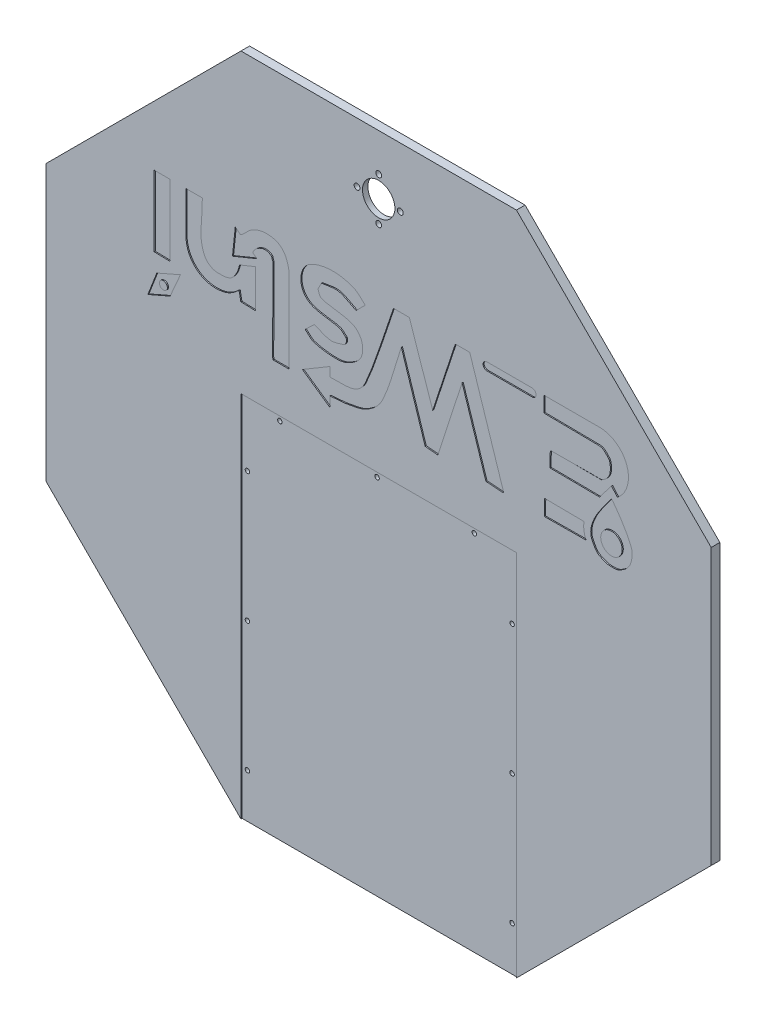
SolidWorks part; units mm, degrees
ref_plane "Front Plane" through (0, 0, 0) normal (0, 0, 1) x (1, 0, 0)
ref_plane "Top Plane" through (0, 0, 0) normal (0, 1, 0) x (1, 0, 0)
ref_plane "Right Plane" through (0, 0, 0) normal (1, 0, 0) x (0, 0, -1)
sketch "Sketch1" plane through (0, 0, 0) normal (0, 0, 1) x (1, 0, 0)
  line L1 (307.8122, -127.5) -> (307.8122, 127.5)
  line L2 (307.8122, 127.5) -> (127.5, 307.8122)
  line L3 (127.5, 307.8122) -> (-127.5, 307.8122)
  line L4 (-127.5, 307.8122) -> (-307.8122, 127.5)
  line L5 (-307.8122, 127.5) -> (-307.8122, -127.5)
  line L6 (-307.8122, -127.5) -> (-127.5, -307.8122)
  line L7 (-127.5, -307.8122) -> (127.5, -307.8122)
  line L8 (127.5, -307.8122) -> (307.8122, -127.5)
  circle A1 centre (0, 0) radius 333.1736 construction
  dimension "D1" = 255
extrude "Boss-Extrude1" add sketch "Sketch1" along normal blind 8
sketch "Sketch2" plane through (0, 0, 0) normal (0, 0, -1) x (-1, 0, 0)
  line L0 (-247.7082, 159.3198) -> (-261.8503, 173.4619)
  line L1 (-247.7082, 159.3198) -> (-159.3198, 247.7082)
  line L2 (-261.8503, 173.4619) -> (-173.4619, 261.8503)
  line L3 (-159.3198, 247.7082) -> (-173.4619, 261.8503)
  line L4 (-307.8122, 127.5) -> (-127.5, 307.8122) construction
  line L6 (-217.6561, 217.6561) -> (-147.1936, 147.1936) construction
  dimension "D1" = 20
  dimension "D2" = 125
  dimension "D3" = 62.5
sketch "Sketch3" plane through (0, 0, 0) normal (0, 0, -1) x (-1, 0, 0)
  line L2 (-127.5, 307.8122) -> (127.5, 307.8122) construction
  circle A0 centre (0.0005, 252.8122) radius 25
  dimension "D1" = 55
extrude "Cut-Extrude1" cut sketch "Sketch3" against normal blind 3
sketch "Sketch4" plane through (0, 0, 3) normal (0, 0, -1) x (-1, 0, 0)
  line L0 (0.0005, 252.8122) -> (0.0005, 272.8122)
  circle A0 centre (0.0005, 252.8122) radius 15
  circle A1 centre (297.8122, -0.0005) radius 2.7032
  circle A2 centre (0.0005, 272.8122) radius 2.7032
  circle A3 centre (-0.0005, -297.8122) radius 2.7032
  circle A4 centre (-297.8122, 0.0005) radius 2.7032
  circle A5 centre (20.0005, 252.8122) radius 2.7032
  circle A6 centre (0.0005, 232.8122) radius 2.7032
  circle A7 centre (-19.9995, 252.8122) radius 2.7032
  point P14 (0, 0)
  point P21 (0.0005, 252.8122)
  dimension "D1" = 30
  dimension "D2" = 20
  dimension "D3" = 5.4065
  dimension "D4" = 4
extrude "Cut-Extrude2" cut sketch "Sketch4" against normal blind 192
sketch "Sketch5" plane through (0, 0, 3) normal (0, 0, -1) x (-1, 0, 0)
  circle A0 centre (0.0005, 252.8122) radius 15
  dimension "D1" = 30
extrude "Cut-Extrude3" cut sketch "Sketch5" against normal blind 192
sketch "Esquisse2" plane through (0, 0, 8) normal (0, 0, 1) x (1, 0, 0)
  line L5 (-127.5, -307.8122) -> (127.5, -307.8122)
  line L6 (127.5, -307.8122) -> (127.5, 33.1878)
  line L7 (127.5, 33.1878) -> (-127.5, 33.1878)
  line L8 (-127.5, 33.1878) -> (-127.5, -307.8122)
  dimension "D1" = 341
extrude "Enlèv. mat.-Extru.2" cut sketch "Esquisse2" against normal blind 1
sketch "Esquisse5" plane through (0, 0, 8) normal (0, 0, 1) x (1, 0, 0)
  line L0 (-908.6273, -471.0171) -> (71.3727, -471.0171) construction
  line L1 (-83.5198, -66.191) -> (-1046.1864, -66.191) construction
  line L2 (-45.2302, 63.2955) -> (-70.6032, 80.9463)
  line L3 (-70.6032, 80.9463) -> (-45.2302, 96.023)
  line L4 (-45.2302, 96.023) -> (-45.2302, 87.6397)
  line L5 (13.7126, 172.142) -> (28.3699, 172.142)
  line L6 (28.3699, 172.142) -> (50.0106, 108.5256)
  line L7 (50.0106, 108.5256) -> (70.9709, 172.142)
  line L8 (70.9709, 172.142) -> (84.2845, 172.142)
  line L9 (84.2845, 172.142) -> (115.8333, 75.0627)
  line L10 (115.8333, 75.0627) -> (99.2857, 76.1658)
  line L11 (99.2857, 76.1658) -> (77.2222, 144.1949)
  line L12 (77.2222, 144.1949) -> (54.791, 75.0627)
  line L13 (54.791, 75.0627) -> (43.0238, 76.1658)
  line L14 (43.0238, 76.1658) -> (20.9603, 144.5627)
  line L15 (-45.2302, 72.4886) -> (-45.2302, 63.2955)
  line L16 (191.9524, 75.4304) -> (153.3413, 75.0627)
  line L17 (153.3413, 75.0627) -> (153.709, 89.7717)
  line L18 (153.709, 89.7717) -> (190.1138, 89.4039)
  line L19 (-213.6482, 69.5468) -> (-193.0556, 78.5191)
  line L21 (-116.5915, 151.6349) -> (-112.8915, 148.6076)
  line L22 (-112.8915, 148.6076) -> (-135.3228, 139.4145)
  line L23 (-135.3228, 139.4145) -> (-132.7487, 164.0521)
  line L24 (-132.7487, 164.0521) -> (-127.9683, 160.3748)
  line L25 (-83.1058, 154.1235) -> (-83.1058, 75.0627)
  line L26 (-68.0291, 114.4092) -> (-59.5714, 122.4992)
  line L28 (-12.5026, 161.478) -> (-20.9603, 153.0203)
  line L29 (-52.9524, 158.9039) -> (-56.2619, 152.6526)
  line L30 (-163.2698, 172.142) -> (-178.3466, 172.142)
  line L31 (-128.7037, 135.7373) -> (-113.9947, 141.6209)
  line L32 (-113.9947, 141.6209) -> (-113.9947, 106.3193)
  line L33 (-113.9947, 106.3193) -> (-127.6005, 106.687)
  line L34 (-127.6005, 106.687) -> (-129.1316, 114.7253)
  line L35 (-193.0556, 106.3193) -> (-207.7646, 106.687)
  line L36 (-207.7646, 106.687) -> (-207.7646, 172.142)
  line L38 (-193.0556, 172.142) -> (-193.0556, 106.3193)
  line L39 (204.455, 116.2478) -> (158.4894, 116.6156)
  line L40 (158.4894, 116.6156) -> (158.8571, 130.5891)
  line L41 (152.9735, 157.8008) -> (152.9735, 172.142)
  line L42 (221.0027, 124.3378) -> (215.4868, 130.5891)
  line L43 (215.4868, 130.5891) -> (204.455, 116.2478)
  line L44 (100.208, 168.8517) -> (142.0716, 168.8517) construction
  line L45 (100.208, 172.4696) -> (142.0716, 172.4696)
  line L46 (100.208, 165.2339) -> (142.0716, 165.2339)
  line L47 (152.9735, 172.142) -> (204.455, 172.142)
  line L48 (-193.0556, 78.5191) -> (-183.4947, 100.4357)
  line L49 (-183.4947, 100.4357) -> (-205.3678, 90.9055)
  line L50 (-205.3678, 90.9055) -> (-213.6482, 69.5468)
  line L51 (-207.7646, 172.142) -> (-193.0556, 172.142)
  line L52 (-83.1058, 75.0627) -> (-97.8148, 75.0627)
  arc A0 (100.208, 172.4696) -> (100.208, 165.2339) centre (100.208, 168.8517) ccw
  arc A1 (142.0716, 165.2339) -> (142.0716, 172.4696) centre (142.0716, 168.8517) ccw
  arc A2 (204.455, 172.142) -> (221.0027, 124.3378) centre (204.455, 145.3759) cw
  circle A3 centre (215.4868, 84.4496) radius 9.9522
  circle A4 centre (-199.2948, 84.0528) radius 3.714
  spline S0 degree 3 poles (-45.2302, 87.6397) (-37.6297, 88.2429) (-29.5905, 86.8338) (-22.4289, 89.4495) (-17.8698, 91.1147) (-14.0634, 95.2853) (-12.1196, 99.7328) (-1.8568, 123.2144) (5.1018, 148.0056) (13.7126, 172.142) knots 0 0 0 0 1 1 1 2 2 2 3 3 3 3
  spline S1 degree 3 poles (20.9603, 144.5627) (15.0767, 127.4022) (11.2015, 109.4157) (3.3095, 93.0812) (0.4439, 87.15) (-4.9929, 82.4587) (-10.664, 79.1076) (-16.1434, 75.8698) (-22.7994, 75.1565) (-29.0503, 73.9595) (-34.3692, 72.941) (-39.8369, 72.9789) (-45.2302, 72.4886) knots 0 0 0 0 1 1 1 2 2 2 3 3 3 4 4 4 4
  spline S2 degree 3 poles (210.3386, 66.605) (206.9308, 68.0249) (206.4987, 67.9587) (203.7196, 69.5468) (202.4215, 70.2885) (200.8086, 72.1986) (200.0423, 73.5918) (198.5065, 76.3842) (196.6536, 79.2433) (196.3651, 82.4172) (195.2023, 95.2079) (208.4293, 110.4123) (215.4868, 120.2928) knots 4 4 4 4 5 5 5 6 6 6 7 7 7 8 8 8 8
  spline S3 degree 3 poles (215.4868, 120.2928) (220.2109, 115.5687) (234.6085, 93.4924) (234.6085, 86.8299) (234.6085, 79.992) (233.36, 74.1427) (227.6217, 69.9145) (225.7403, 68.5282) (221.7566, 65.8695) (219.164, 65.8695) (216.212, 65.8695) (213.0635, 65.4696) (210.3386, 66.605) knots 0 0 0 0 1 1 1 2 2 2 3 3 3 4 4 4 4
  spline S4 degree 2 poles (-32.3598, 119.9251) (-28.8372, 122.3396) (-30.1534, 126.5441) knots 0 0 0 1 1 1
  spline S6 degree 3 poles (-97.8148, 75.0627) (-97.9341, 75.7987) (-98.1725, 76.525) (-98.1726, 77.2706) (-98.1768, 102.7662) (-97.8207, 128.261) (-97.8278, 153.7566) (-97.8278, 153.93) (-98.1337, 153.9634) (-98.1938, 154.126) (-98.5034, 154.963) (-98.6081, 155.8664) (-98.9177, 156.7034) (-99.2183, 157.5163) (-100.0189, 158.0817) (-100.748, 158.5503) (-106.0543, 161.9607) (-114.6964, 157.2357) (-116.5915, 151.6349) knots 0 0 0 0 1 1 1 2 2 2 3 3 3 4 4 4 5 5 5 6 6 6 6
  spline S7 degree 3 poles (-127.9683, 160.3748) (-124.8482, 161.6229) (-121.0743, 167.5504) (-116.5688, 169.9357) (-112.979, 171.8361) (-108.8781, 173.1178) (-104.8016, 173.2452) (-91.4146, 173.6635) (-85.2679, 167.0958) (-83.1058, 154.1235) knots 0 0 0 0 1 1 1 2 2 2 3 3 3 3
  spline S8 degree 3 poles (-56.2619, 152.6526) (-55.1587, 150.6914) (-55.0563, 147.567) (-52.9524, 146.769) (-43.8032, 143.2986) (-33.3051, 144.2749) (-24.2698, 140.5177) (-20.4251, 138.9189) (-17.2249, 135.2415) (-15.8122, 131.3246) (-14.3145, 127.172) (-14.3932, 122.1231) (-16.1799, 118.0865) (-17.9694, 114.0436) (-21.9383, 111.1491) (-25.7407, 108.8933) (-29.3759, 106.7369) (-33.65, 105.307) (-37.8757, 105.2161) (-45.2935, 105.0566) (-52.8421, 105.9942) (-59.9392, 108.1579) (-63.199, 109.1517) (-65.3325, 112.3254) (-68.0291, 114.4092) knots 0 0 0 0 1 1 1 2 2 2 3 3 3 4 4 4 5 5 5 6 6 6 7 7 7 8 8 8 8
  spline S9 degree 3 poles (-59.5714, 122.4992) (-54.5459, 120.7831) (-49.7816, 117.8511) (-44.4947, 117.351) (-40.3781, 116.9616) (-36.4048, 119.0671) (-32.3598, 119.9251) knots 0 0 0 0 1 1 1 2 2 2 2
  spline S10 degree 3 poles (-30.1534, 126.5441) (-32.2372, 128.1376) (-33.9077, 130.5209) (-36.4048, 131.3246) (-44.7578, 134.0129) (-54.1023, 133.3322) (-62.1455, 136.8404) (-66.1209, 138.5744) (-69.5041, 142.3197) (-70.9709, 146.4013) (-72.5467, 150.7862) (-72.2619, 156.0206) (-70.6032, 160.3748) (-69.1208, 164.266) (-65.8893, 167.7453) (-62.1455, 169.5679) (-56.1566, 172.4836) (-49.3167, 173.9184) (-42.6561, 173.9806) (-35.9014, 174.0438) (-29.0388, 172.5229) (-22.7989, 169.9357) (-18.6961, 168.2345) (-15.9347, 164.2972) (-12.5026, 161.478) knots 0 0 0 0 1 1 1 2 2 2 3 3 3 4 4 4 5 5 5 6 6 6 7 7 7 8 8 8 8
  spline S11 degree 3 poles (-20.9603, 153.0203) (-26.3536, 155.4718) (-31.3136, 159.3033) (-37.1402, 160.3748) (-42.3464, 161.3323) (-47.6817, 159.3942) (-52.9524, 158.9039) knots 0 0 0 0 1 1 1 2 2 2 2
  spline S12 degree 3 poles (-129.1316, 114.7253) (-130.823, 114.1635) (-131.7324, 112.9431) (-133.1797, 111.7877) (-136.3656, 109.2444) (-139.861, 107.501) (-143.8491, 106.6508) (-162.1459, 102.7501) (-178.0928, 114.7481) (-178.3867, 133.8987) (-178.5823, 146.645) (-178.3599, 159.3942) (-178.3466, 172.142) knots 0 0 0 0 1 1 1 2 2 2 3 3 3 4 4 4 4
  spline S13 degree 3 poles (-163.2698, 172.142) (-163.0696, 149.9129) (-167.1073, 142.5383) (-161.7989, 128.3828) (-159.7986, 123.0484) (-154.4319, 119.1896) (-148.5609, 119.1896) (-144.8852, 119.1896) (-138.8525, 119.233) (-135.6905, 122.1314) (-131.6775, 125.81) (-129.9789, 130.6363) (-128.7037, 135.7373) knots 0 0 0 0 1 1 1 2 2 2 3 3 3 4 4 4 4
  spline S14 degree 3 poles (158.8571, 130.5891) (159.5926, 130.7117) (160.3179, 130.9511) (161.0635, 130.9568) (176.1398, 131.0737) (191.2174, 130.8353) (206.2937, 130.9568) (206.467, 130.9582) (206.5063, 131.247) (206.6614, 131.3246) (210.9878, 133.4878) (214.206, 136.8381) (214.3836, 141.9886) (214.4585, 144.162) (214.749, 149.3454) (212.545, 151.5494) (211.2963, 152.7981) (208.1521, 156.7951) (205.5582, 157.0653) (200.6801, 157.5734) (195.7533, 157.3644) (190.8492, 157.433) (178.2246, 157.6096) (165.5988, 157.6782) (152.9735, 157.8008) knots 0 0 0 0 1 1 1 2 2 2 3 3 3 4 4 4 5 5 5 6 6 6 7 7 7 8 8 8 8
  spline S15 degree 2 poles (190.1138, 89.4039) (188.9077, 82.1187) (191.9524, 75.4304) knots 0 0 0 1 1 1
  point P70 (121.1398, 168.8517)
extrude "Enlèv. mat.-Extru.4" cut sketch "Esquisse5" against normal blind 1
sketch "Esquisse8" plane through (0, 0, 7) normal (0, 0, 1) x (1, 0, 0)
  circle A0 centre (-92.5, 28.1878) radius 2.05
  circle A1 centre (-2.5, 28.1878) radius 2.05
  circle A2 centre (87.5, 28.1878) radius 2.05
  circle A3 centre (122.5, -26.8122) radius 2.05
  circle A4 centre (122.5, -146.8122) radius 2.05
  circle A5 centre (122.5, -266.8122) radius 2.05
  circle A6 centre (-122.5, -266.8122) radius 2.05
  circle A7 centre (-122.5, -146.8122) radius 2.05
  circle A8 centre (-122.5, -26.8122) radius 2.05
extrude "Enlèv. mat.-Extru.5" cut sketch "Esquisse8" against normal blind 20
